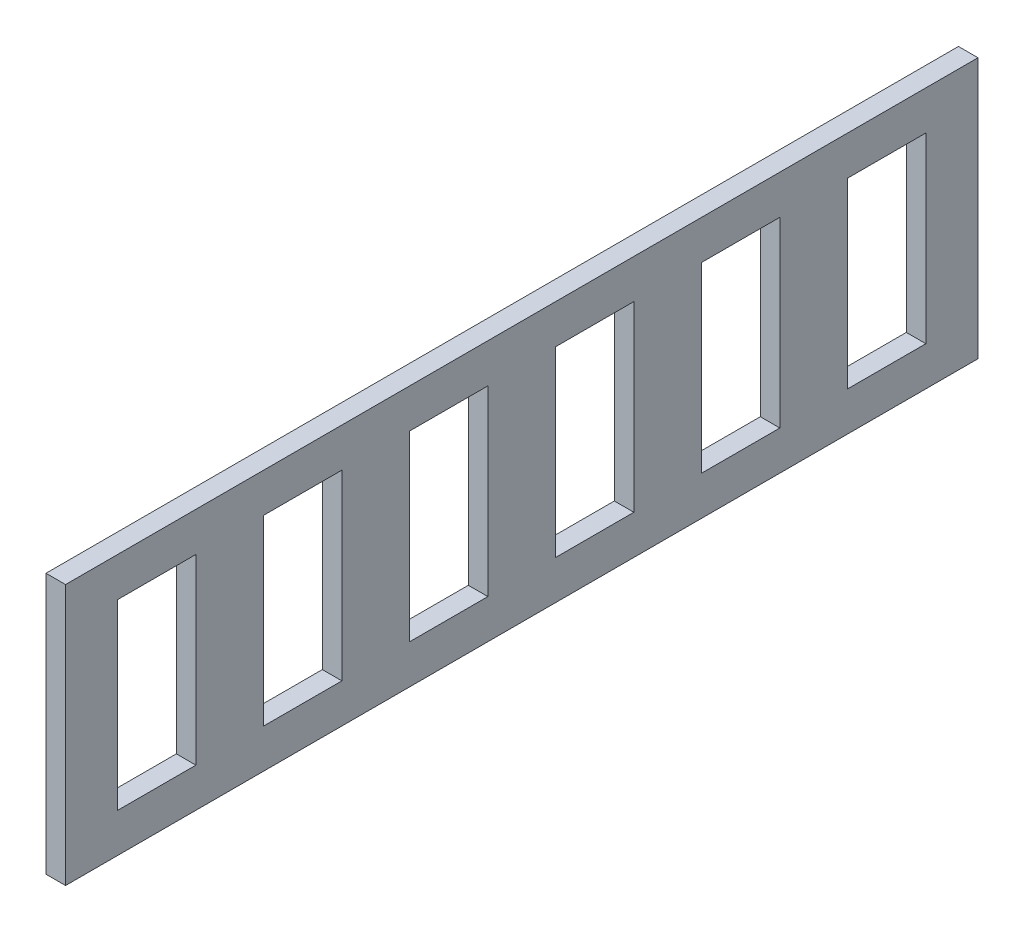
SolidWorks part; units mm, degrees
ref_plane "Front Plane" through (0, 0, 0) normal (0, 0, 1) x (1, 0, 0)
ref_plane "Top Plane" through (0, 0, 0) normal (0, 1, 0) x (1, 0, 0)
ref_plane "Right Plane" through (0, 0, 0) normal (1, 0, 0) x (0, 0, -1)
sketch "Sketch1" plane through (0, 0, 0) normal (1, 0, 0) x (0, 0, -1)
  line L1 (-350, 0) -> (350, 0)
  line L2 (-350, 0) -> (-350, 200)
  line L3 (-350, 200) -> (350, 200)
  line L4 (350, 0) -> (350, 200)
  line L5 (-310, 170) -> (-250, 170)
  line L6 (-310, 170) -> (-310, 30)
  line L7 (-310, 30) -> (-250, 30)
  line L8 (-250, 170) -> (-250, 30)
  line L52 (-310, 170) -> (-250, 170) construction
  line L89 (-198, 170) -> (-198, 30)
  line L90 (-198, 170) -> (-138, 170)
  line L91 (-138, 170) -> (-138, 30)
  line L92 (-198, 30) -> (-138, 30)
  line L93 (-86, 170) -> (-86, 30)
  line L94 (-86, 170) -> (-26, 170)
  line L95 (-26, 170) -> (-26, 30)
  line L96 (-86, 30) -> (-26, 30)
  line L97 (26, 170) -> (26, 30)
  line L98 (26, 170) -> (86, 170)
  line L99 (86, 170) -> (86, 30)
  line L100 (26, 30) -> (86, 30)
  line L101 (138, 170) -> (138, 30)
  line L102 (138, 170) -> (198, 170)
  line L103 (198, 170) -> (198, 30)
  line L104 (138, 30) -> (198, 30)
  line L105 (250, 170) -> (250, 30)
  line L106 (250, 170) -> (310, 170)
  line L107 (310, 170) -> (310, 30)
  line L108 (250, 30) -> (310, 30)
  point P4 (0, 0)
  point P10 (-280, 170)
  dimension "D1" = 700
  dimension "D2" = 200
  dimension "D3" = 30
  dimension "D4" = 30
  dimension "D5" = 40
  dimension "D6" = 60
  dimension "D8" = 40
  dimension "D7" = 6
extrude "Boss-Extrude1" add sketch "Sketch1" along normal blind 15
